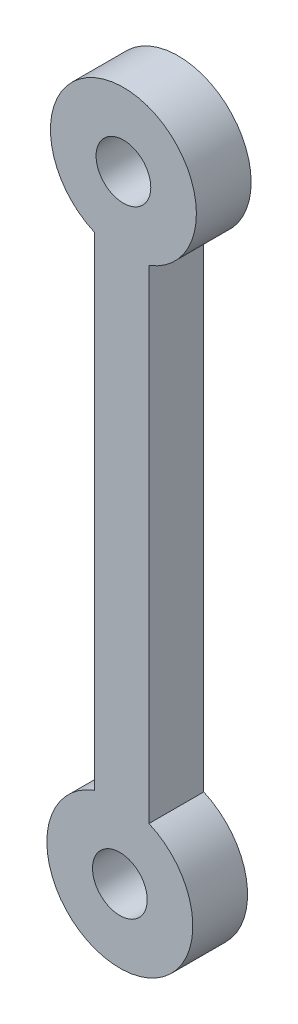
SolidWorks part; units mm, degrees
ref_plane "Front Plane" through (0, 0, 0) normal (0, 0, 1) x (1, 0, 0)
ref_plane "Top Plane" through (0, 0, 0) normal (0, 1, 0) x (1, 0, 0)
ref_plane "Right Plane" through (0, 0, 0) normal (1, 0, 0) x (0, 0, -1)
sketch "Sketch1" plane through (0, 0, 0) normal (0, 0, 1) x (1, 0, 0)
  line L0 (0, 0) -> (0, 26.5)
  line L2 (3, 26.4209) -> (3, -0.0791)
  arc A0 (0, 26.5) -> (3, 26.4209) centre (1.5978, 30.167) cw
  arc A1 (0, 0) -> (3, -0.0791) centre (1.4022, -3.7462) ccw
  circle A2 centre (1.5978, 30.167) radius 1.5
  circle A3 centre (1.4022, -3.7462) radius 1.5
  dimension "D1" = 3
  dimension "D3" = 4
  dimension "D4" = 3
  dimension "D2" = 26.5
extrude "Boss-Extrude1" add sketch "Sketch1" along normal blind 3
